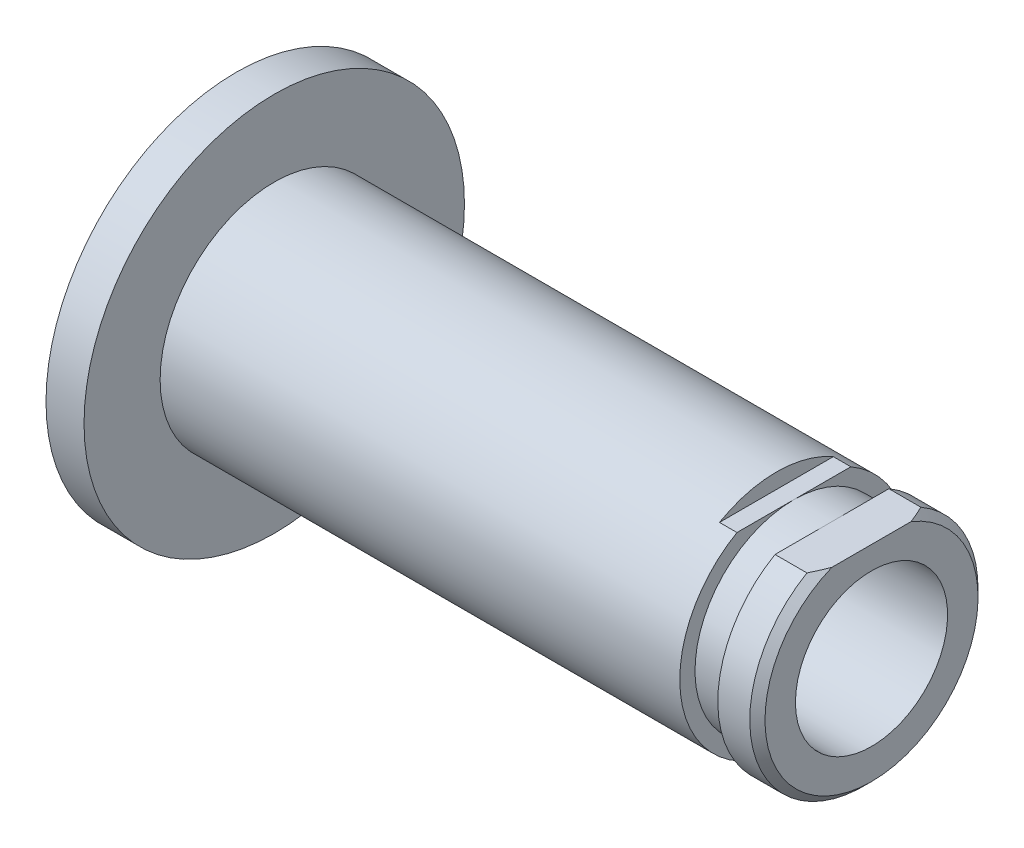
SolidWorks part; units mm, degrees
material "Delrin 2700 NC010, Low Viscosity Acetal Copolymer (SS)"
ref_plane "Front" through (0, 0, 0) normal (0, 0, 1) x (1, 0, 0)
ref_plane "Top" through (0, 0, 0) normal (0, 1, 0) x (1, 0, 0)
ref_plane "Right" through (0, 0, 0) normal (1, 0, 0) x (0, 0, -1)
sketch "Sketch1" plane through (0, 0, 0) normal (0, 0, 1) x (1, 0, 0)
  line L0 (0, 0) -> (133.2147, 0) construction
  line L1 (0, 31.75) -> (0, 6.477)
  line L2 (6.35, 19.05) -> (106.045, 19.05)
  line L3 (106.045, 19.05) -> (106.045, 12.7)
  line L4 (106.045, 12.7) -> (44.45, 12.7)
  line L5 (0, 31.75) -> (6.35, 31.75)
  line L6 (6.35, 31.75) -> (6.35, 19.05)
  line L7 (44.45, 12.7) -> (44.45, 6.477)
  line L8 (44.45, 6.477) -> (0, 6.477)
  dimension "D1" = 38.1
  dimension "D2" = 25.4
  dimension "D3" = 99.695
  dimension "D4" = 6.35
  dimension "D5" = 63.5
  dimension "D6" = 12.954
  dimension "D7" = 44.45
revolve "Revolve1" add sketch "Sketch1" angle 360 about L0
sketch "Sketch2" plane through (106.045, 0, 0) normal (1, 0, 0) x (0, 0, -1)
  line L1 (-79.4479, 72.0592) -> (82.8697, 72.0592)
  line L2 (-79.4479, 72.0592) -> (-79.4479, 16.51)
  line L3 (-79.4479, 16.51) -> (82.8697, 16.51)
  line L4 (82.8697, 72.0592) -> (82.8697, 16.51)
  dimension "D1" = 16.51
extrude "Cut-Extrude1" cut sketch "Sketch2" against normal offset from surface (15.875 mm away) 83.82 up to face at (6.35, 0, 31.75)
sketch "Sketch3" plane through (0, 0, 0) normal (0, 0, 1) x (1, 0, 0)
  line L0 (93.091, 16.51) -> (93.091, 19.685)
  line L1 (106.045, 16.51) -> (90.17, 16.51) construction
  line L2 (93.091, 19.685) -> (99.441, 19.685)
  line L3 (93.091, 16.51) -> (99.441, 16.51)
  line L4 (0, 0) -> (61.6524, 0) construction
  line L7 (99.441, 19.685) -> (99.441, 16.51)
  line L8 (96.266, 16.51) -> (96.266, 23.2552) construction
  line L9 (90.17, 16.51) -> (90.17, 19.05) construction
  dimension "D1" = 6.096
  dimension "D2" = 6.35
  dimension "D3" = 3.175
revolve "Cut-Revolve1" cut sketch "Sketch3" angle 360 about L4
chamfer "Chamfer1" distance 1.27 angle 45 1 edges at (106.045, -19.05, 0)
